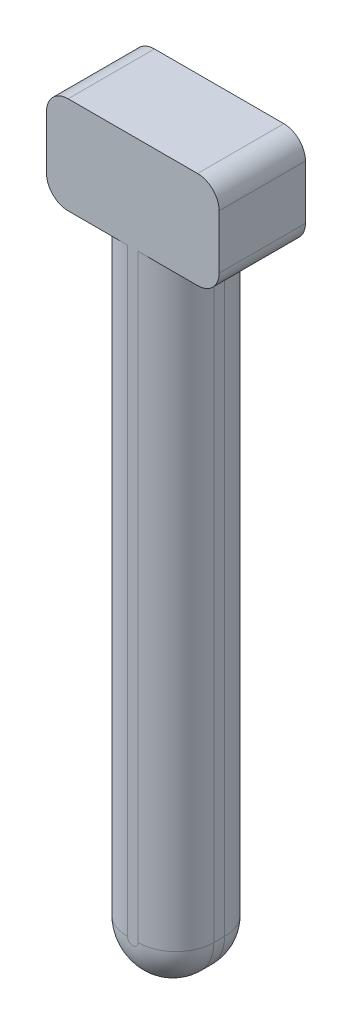
SolidWorks part; units mm, degrees
ref_plane "Front Plane" through (0, 0, 0) normal (0, 0, 1) x (1, 0, 0)
ref_plane "Top Plane" through (0, 0, 0) normal (0, 1, 0) x (1, 0, 0)
ref_plane "Right Plane" through (0, 0, 0) normal (1, 0, 0) x (0, 0, -1)
sketch "Sketch1" plane through (0, 0, 0) normal (0, 0, 1) x (1, 0, 0)
  line L0 (0, 0) -> (0, -30) construction
  line L1 (-4, -2.25) -> (4, -2.25)
  line L2 (-4, -2.25) -> (-4, 2.25)
  line L3 (-4, 2.25) -> (4, 2.25)
  line L4 (4, -2.25) -> (4, 2.25)
  line L5 (-4, -2.25) -> (4, 2.25) construction
  line L6 (-4, 2.25) -> (4, -2.25) construction
  line L7 (-2, 0) -> (-2, -30)
  line L8 (2, 0) -> (2, -30)
  arc A0 (-2, 0) -> (2, 0) centre (0, 0) cw
  arc A1 (-2, -30) -> (2, -30) centre (0, -30) ccw
  point P0 (0, 0)
  dimension "D1" = 30
  dimension "D2" = 4.5
  dimension "D3" = 8
  dimension "D4" = 2
  dimension "D5" = 2
extrude "Boss-Extrude1" add sketch "Sketch1" along normal blind 4 contours L7 A1 L8 L1 | A0 L7 L1 L8 | L7 A0 L8 L1 L4 L3 L2
fillet "Fillet1" radius 1.75 6 edges at (-2, -16.125, 0) (0, -32, 0) (-2, -16.125, 4) (0, -32, 4) (2, -16.125, 0) (2, -16.125, 4)
fillet "Fillet2" radius 1 4 edges at (-4, -2.25, 2) (4, -2.25, 2) (4, 2.25, 2) (-4, 2.25, 2)
